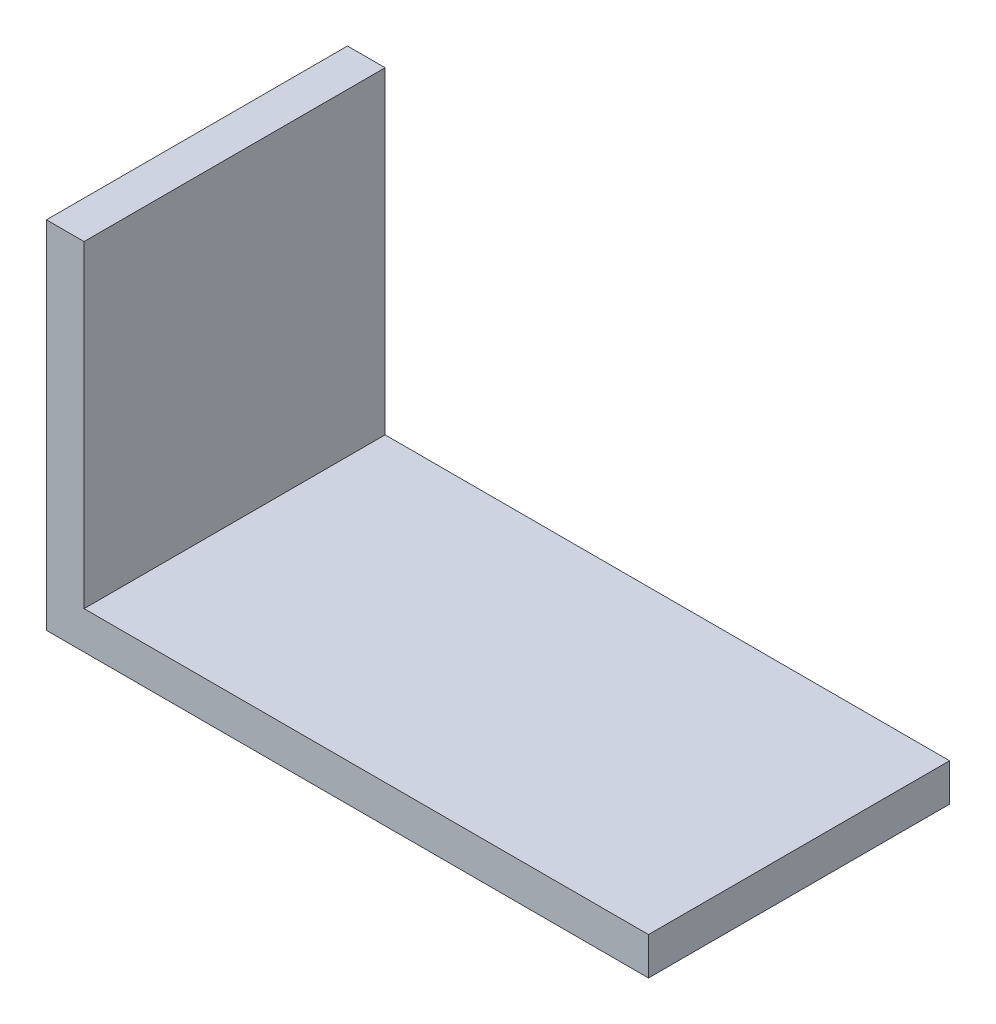
SolidWorks part; units mm, degrees
material "6061 Alloy"
ref_plane "Front Plane" through (0, 0, 0) normal (0, 0, 1) x (1, 0, 0)
ref_plane "Top Plane" through (0, 0, 0) normal (0, 1, 0) x (1, 0, 0)
ref_plane "Right Plane" through (0, 0, 0) normal (1, 0, 0) x (0, 0, -1)
sketch "Sketch1" plane through (0, 0, 0) normal (0, 0, 1) x (1, 0, 0)
  line L0 (0, 0) -> (0, 30)
  line L1 (0, 0) -> (50.8, 0)
  line L2 (3.175, 3.175) -> (50.8, 3.175)
  line L3 (3.175, 3.175) -> (3.175, 30)
  line L4 (3.175, 30) -> (0, 30)
  line L5 (50.8, 3.175) -> (50.8, 0)
  dimension "D1" = 30
  dimension "D2" = 50.8
  dimension "D3" = 3.175
extrude "Boss-Extrude1" add sketch "Sketch1" along normal blind 25.4
other "Hole1" parameters "D1"=3.175
sketch "Sketch2" plane through (-411, 0, 92.3156) normal (0, -1, 0) x (-1, 0, 0)
  circle A0 centre (-436.4, 79.6156) radius 8.763
other "Hole2" parameters "D1"=3.175
sketch "Sketch3" plane through (-411, 0, 92.3156) normal (0, -1, 0) x (-1, 0, 0)
  circle A0 centre (-450.624, 79.6156) radius 1.397
